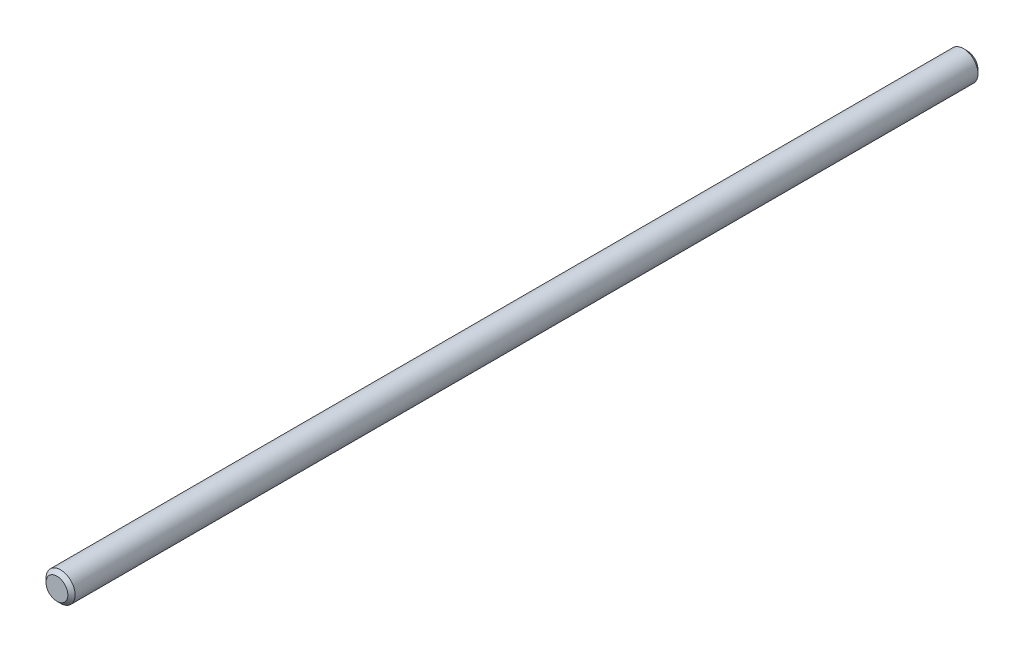
SolidWorks part; units mm, degrees
ref_plane "Piano frontale" through (0, 0, 0) normal (0, 0, 1) x (1, 0, 0)
ref_plane "Piano superiore" through (0, 0, 0) normal (0, 1, 0) x (1, 0, 0)
ref_plane "Piano destro" through (0, 0, 0) normal (1, 0, 0) x (0, 0, -1)
sketch "Schizzo1" plane through (0, 0, 0) normal (0, 0, 1) x (1, 0, 0)
  circle A0 centre (0, 0) radius 4
  dimension "D1" = 8
extrude "Estrusione-Estrusione1" add sketch "Schizzo1" along normal blind 250
chamfer "Smusso1" distance 1 angle 45 2 edges at (4, 0, 250) (4, 0, 0)
